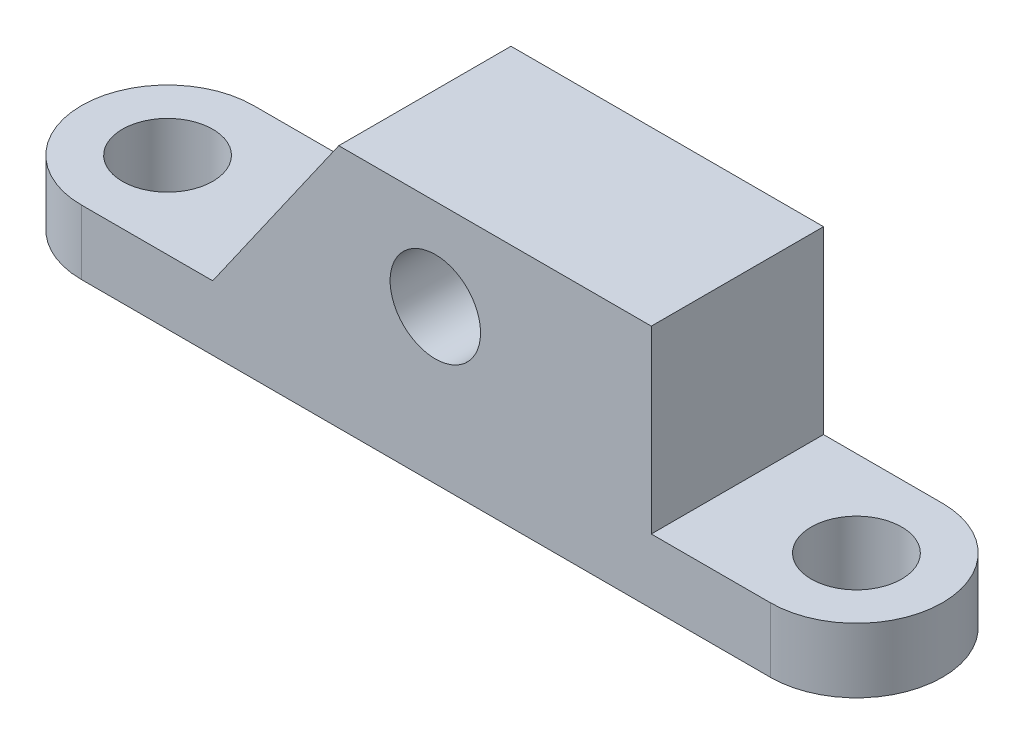
SolidWorks part; units mm, degrees
ref_plane "Front" through (0, 0, 0) normal (0, 0, 1) x (1, 0, 0)
ref_plane "Top" through (0, 0, 0) normal (0, 1, 0) x (1, 0, 0)
ref_plane "Right" through (0, 0, 0) normal (1, 0, 0) x (0, 0, -1)
sketch "Sketch1" plane through (0, 0, 0) normal (0, 1, 0) x (1, 0, 0)
  line L1 (0, -4) -> (32, -4)
  line L2 (0, 4) -> (32, 4)
  circle A0 centre (0, 0) radius 2.1
  circle A1 centre (32, 0) radius 2.1
  arc A2 (32, -4) -> (32, 4) centre (32, 0) ccw
  arc A3 (0, 4) -> (0, -4) centre (0, 0) ccw
extrude "Boss-Extrude1" add sketch "Sketch1" along normal blind 3
sketch "Sketch2" plane through (0, 0, 4) normal (0, 0, 1) x (1, 0, 0)
  line L3 (26.4706, 11.3632) -> (11.953, 11.3632)
  line L4 (6.097, 3) -> (20.6146, 3)
  line L5 (26.4706, 11.3632) -> (26.4706, 3)
  line L7 (0, 3) -> (32, 3) construction
  line L10 (6.097, 3) -> (11.953, 11.3632)
  line L11 (26.4706, 3) -> (20.6146, 3)
  circle A0 centre (16.4384, 7.1271) radius 2.1
  dimension "D3" = 55
extrude "Boss-Extrude2" add sketch "Sketch2" against normal blind 8
